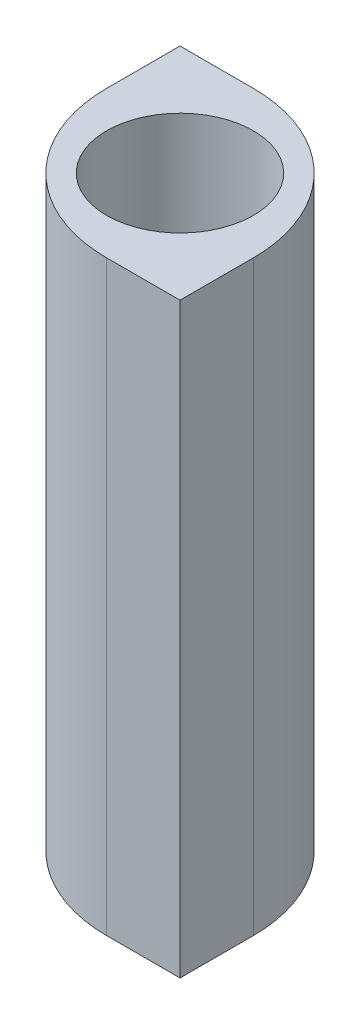
SolidWorks part; units mm, degrees
ref_plane "前基準面" through (0, 0, 0) normal (0, 0, 1) x (1, 0, 0)
ref_plane "上基準面" through (0, 0, 0) normal (0, 1, 0) x (1, 0, 0)
ref_plane "右基準面" through (0, 0, 0) normal (1, 0, 0) x (0, 0, -1)
sketch "草圖1" plane through (0, 0, 0) normal (0, 1, 0) x (1, 0, 0)
  circle A0 centre (0, 0) radius 6
  dimension "D1" = 12
extrude "填料-伸長1" add sketch "草圖1" along normal blind 40
sketch "草圖2" plane through (0, 40, 0) normal (0, 1, 0) x (1, 0, 0)
  circle A0 centre (0, 0) radius 5
  dimension "D1" = 10
extrude "除料-伸長2" cut sketch "草圖2" against normal blind 30
sketch "草圖3" plane through (0, 0, 0) normal (0, -1, 0) x (1, 0, 0)
  circle A0 centre (0, 0) radius 2.5
  dimension "D1" = 5
extrude "除料-伸長4" cut sketch "草圖3" against normal blind 10
sketch "草圖5" plane through (0, 0, 0) normal (0, 1, 0) x (1, 0, 0)
  circle A0 centre (0, 0) radius 6
extrude "伸長-薄件1" add sketch "草圖5" along normal blind 40 thin
sketch "草圖6" plane through (0, 40, 0) normal (0, 1, 0) x (1, 0, 0)
  line L1 (6, 6) -> (-6, 6)
  line L2 (6, 6) -> (6, -6)
  line L3 (6, -6) -> (-6, -6)
  line L4 (-6, 6) -> (-6, -6)
  line L5 (6, 6) -> (-6, -6) construction
  line L6 (6, -6) -> (-6, 6) construction
  point P0 (0, 0)
  dimension "D1" = 12
  dimension "D2" = 12
extrude "伸長-薄件2" add sketch "草圖6" against normal blind 40 thin
sketch "草圖7" plane through (0, 40, 0) normal (0, 1, 0) x (1, 0, 0)
  line L1 (-7.5, -7.5) -> (7.5, -7.5)
  line L2 (-7.5, -7.5) -> (-7.5, 7.5)
  line L3 (-7.5, 7.5) -> (7.5, 7.5)
  line L4 (7.5, -7.5) -> (7.5, 7.5)
  line L5 (-7.5, -7.5) -> (7.5, 7.5) construction
  line L6 (-7.5, 7.5) -> (7.5, -7.5) construction
  point P0 (0, 0)
  dimension "D1" = 15
  dimension "D2" = 15
extrude "除料-伸長-薄件2" cut sketch "草圖7" against normal through all thin
fillet "圓角1" radius 10 2 edges at (7.5, 20, -7.5) (-7.5, 20, 7.5)
